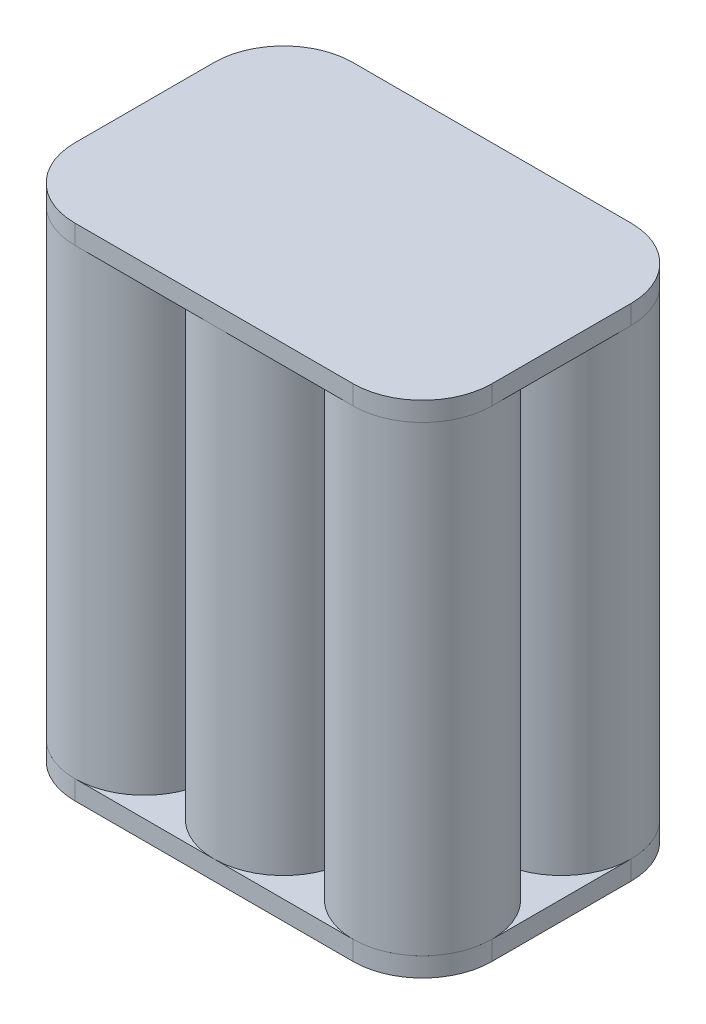
SolidWorks part; units mm, degrees
ref_plane "Front Plane" through (0, 0, 0) normal (0, 0, 1) x (1, 0, 0)
ref_plane "Top Plane" through (0, 0, 0) normal (0, 1, 0) x (1, 0, 0)
ref_plane "Right Plane" through (0, 0, 0) normal (1, 0, 0) x (0, 0, -1)
sketch "Sketch1" plane through (0, 0, 0) normal (0, 1, 0) x (1, 0, 0)
  circle A0 centre (0, 0) radius 7.2233
  circle A1 centre (14.45, 0) radius 7.2233
  circle A2 centre (28.9, 0) radius 7.2233
  circle A3 centre (14.45, 14.45) radius 7.2233
  circle A4 centre (28.9, 14.45) radius 7.2233
  circle A5 centre (0, 14.45) radius 7.2233
  dimension "D1" = 14.4467
  dimension "D2" = 3
  dimension "D3" = 2
extrude "Boss-Extrude1" add sketch "Sketch1" along normal blind 52
sketch "Sketch2" plane through (0, 52, 0) normal (0, 1, 0) x (1, 0, 0)
  line L1 (-7.2233, 21.6733) -> (36.1233, 21.6733)
  line L2 (-7.2233, 21.6733) -> (-7.2233, -7.2233)
  line L3 (-7.2233, -7.2233) -> (36.1233, -7.2233)
  line L4 (36.1233, 21.6733) -> (36.1233, -7.2233)
  circle A0 centre (0, 14.45) radius 7.2233 construction
  circle A1 centre (0, 0) radius 7.2233 construction
  circle A2 centre (28.9, 14.45) radius 7.2233 construction
extrude "Boss-Extrude2" add sketch "Sketch2" against normal blind 2
sketch "Sketch3" plane through (0, 0, 0) normal (0, -1, 0) x (1, 0, 0)
  line L0 (-7.2233, -14.45) -> (-7.2233, 0) construction
  line L1 (-7.2233, 7.2233) -> (36.1233, 7.2233)
  line L2 (-7.2233, 7.2233) -> (-7.2233, -21.6733)
  line L3 (-7.2233, -21.6733) -> (36.1233, -21.6733)
  line L4 (36.1233, 7.2233) -> (36.1233, -21.6733)
  line L5 (14.45, -21.6733) -> (0, -21.6733) construction
  line L6 (36.1233, 0) -> (36.1233, -14.45) construction
  line L7 (14.45, 7.2233) -> (28.9, 7.2233) construction
extrude "Boss-Extrude3" add sketch "Sketch3" against normal blind 2
fillet "Fillet1" radius 7.22 8 edges at (36.1233, 51, 7.2233) (36.1233, 1, 7.2233) (-7.2233, 51, 7.2233) (-7.2233, 1, 7.2233) (-7.2233, 51, -21.6733) (36.1233, 51, -21.6733) (36.1233, 1, -21.6733) (-7.2233, 1, -21.6733)
